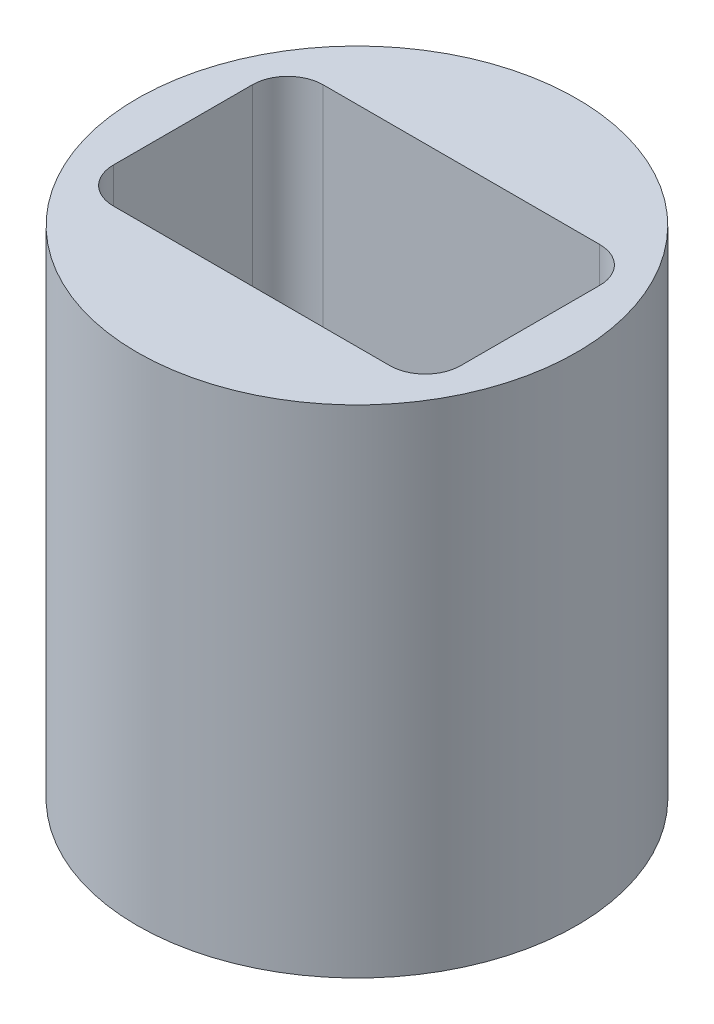
SolidWorks part; units mm, degrees
ref_plane "Plano frontal" through (0, 0, 0) normal (0, 0, 1) x (1, 0, 0)
ref_plane "Plano superior" through (0, 0, 0) normal (0, 1, 0) x (1, 0, 0)
ref_plane "Plano direito" through (0, 0, 0) normal (1, 0, 0) x (0, 0, -1)
sketch "Esboço1" plane through (0, 0, 0) normal (0, 1, 0) x (1, 0, 0)
  circle A0 centre (0, 0) radius 3.1
  dimension "D1" = 6.2
extrude "Ressalto-extrusão1" add sketch "Esboço1" along normal blind 7
sketch "Esboço2" plane through (0, 7, 0) normal (0, 1, 0) x (1, 0, 0)
  line L0 (0, 3.2355) -> (0, -3.3985) construction
  line L1 (-3.3985, 0) -> (3.386, 0) construction
  line L3 (-1.9563, -1.48) -> (1.9437, -1.48)
  line L4 (-2.4563, -0.98) -> (-2.4563, 0.98)
  line L5 (-1.9563, 1.48) -> (1.9437, 1.48)
  line L6 (2.4437, -0.98) -> (2.4437, 0.98)
  line L7 (-2.4563, -1.48) -> (2.4437, 1.48) construction
  line L8 (-2.4563, 1.48) -> (2.4437, -1.48) construction
  arc A0 (-2.4563, 0.98) -> (-1.9563, 1.48) centre (-1.9563, 0.98) cw
  arc A1 (2.4437, 0.98) -> (1.9437, 1.48) centre (1.9437, 0.98) ccw
  arc A2 (2.4437, -0.98) -> (1.9437, -1.48) centre (1.9437, -0.98) cw
  arc A3 (-2.4563, -0.98) -> (-1.9563, -1.48) centre (-1.9563, -0.98) ccw
  point P5 (-0.0063, 0)
  dimension "D3" = 0.5
  dimension "D1" = 4.9
  dimension "D2" = 2.96
extrude "Corte-extrusão1" cut sketch "Esboço2" against normal through all
